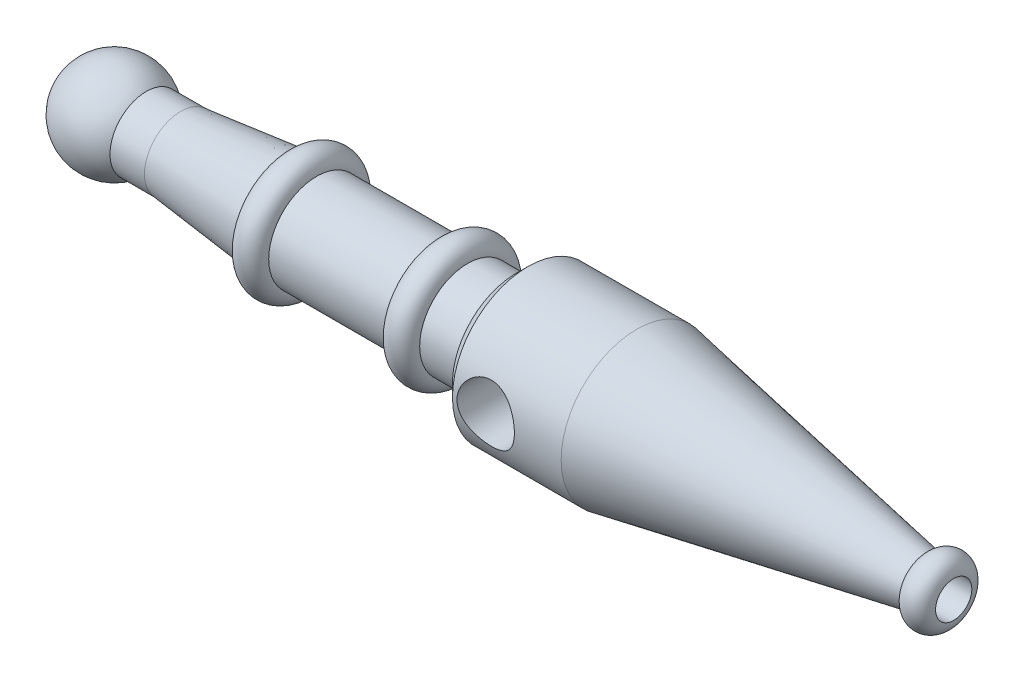
SolidWorks part; units mm, degrees
ref_plane "Front Plane" through (0, 0, 0) normal (0, 0, 1) x (1, 0, 0)
ref_plane "Top Plane" through (0, 0, 0) normal (0, 1, 0) x (1, 0, 0)
ref_plane "Right Plane" through (0, 0, 0) normal (1, 0, 0) x (0, 0, -1)
sketch "Sketch1" plane through (0, 0, 0) normal (0, 1, 0) x (1, 0, 0)
  line L0 (0, 0) -> (139, 0)
  line L1 (0, 0) -> (0, 3)
  line L2 (5.2915, 6) -> (11, 6)
  line L3 (11, 6) -> (28.5, 7.927)
  line L4 (139, 3) -> (0, 3)
  line L5 (66.5, 0) -> (86.5, 0)
  line L7 (33.5, 7.927) -> (53.5, 7.927)
  line L11 (58.5, 0) -> (66.5, 0)
  line L13 (58.5, 7.927) -> (66.5, 7.927)
  line L15 (86.5, 12.5) -> (66.5, 12.5)
  line L16 (66.5, 12.5) -> (66.5, 7.927)
  line L17 (139, 0) -> (139, 3)
  line L18 (134.1585, 3.8761) -> (86.5, 12.5)
  line L19 (139, 0) -> (134, 0)
  line L21 (0, 0) -> (-8, 0)
  arc A0 (28.5, 7.927) -> (33.5, 7.927) centre (31, 7.927) cw
  arc A1 (53.5, 7.927) -> (58.5, 7.927) centre (56, 7.927) cw
  arc A2 (134.1585, 3.8761) -> (139, 3) centre (136.5, 3) cw
  arc A3 (5.2915, 6) -> (-8, 0) centre (0, 0) ccw
  dimension "D7" = 2.5
  dimension "D15" = 2.5
  dimension "D16" = 16
  dimension "D1" = 139
  dimension "D6" = 5
  dimension "D8" = 20
  dimension "D9" = 8
  dimension "D10" = 20
  dimension "D11" = 12.5
  dimension "D12" = 3
  dimension "D13" = 5
revolve "Revolve1" add sketch "Sketch1" angle 360 about L0
chamfer "Chamfer1" distance 2 angle 45 1 edges at (66.5, 0, 12.5)
sketch "Sketch2" plane through (0, 0, 0) normal (0, 0, 1) x (1, 0, 0)
  circle A0 centre (74, 0) radius 4.75
  dimension "D2" = 9.5
extrude "Cut-Extrude1" cut sketch "Sketch2" against normal through all and the other way through all
